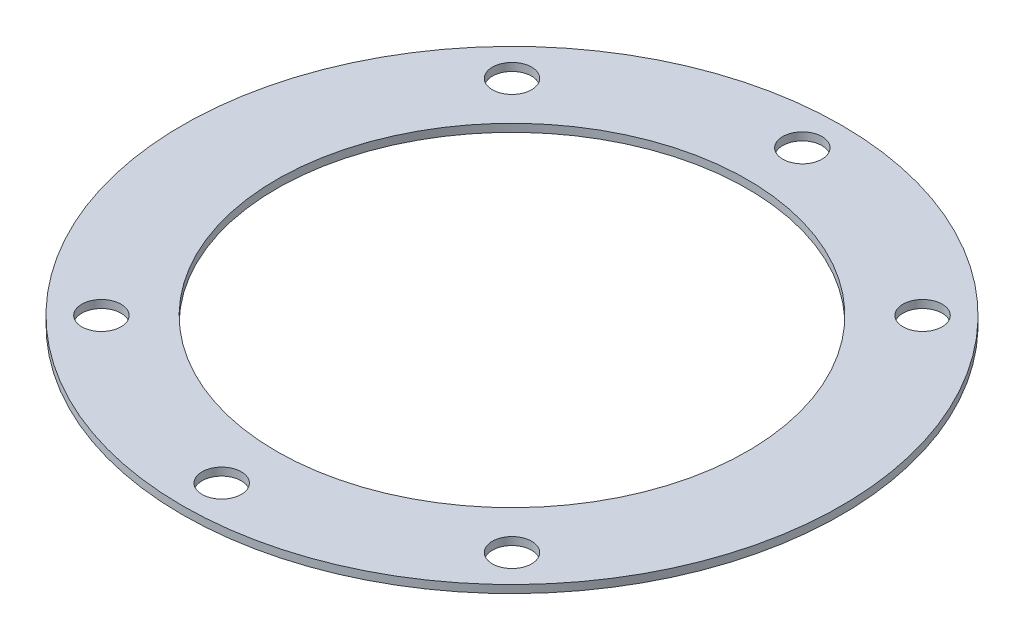
SolidWorks part; units mm, degrees
material "Alliage 1060"
ref_plane "Face" through (0, 0, 0) normal (0, 0, 1) x (1, 0, 0)
ref_plane "Dessus" through (0, 0, 0) normal (0, 1, 0) x (1, 0, 0)
ref_plane "Droite" through (0, 0, 0) normal (1, 0, 0) x (0, 0, -1)
sketch "Esquisse1" plane through (0, 0, 0) normal (1, 0, 0) x (0, 0, -1)
  line L0 (0, 0) -> (0, -70.5308) construction
  line L1 (-30, 0) -> (-42, 0)
  line L3 (-30, 0) -> (-30, 1)
  line L4 (-30, 1) -> (-42, 1)
  line L5 (-42, 1) -> (-42, 0)
  dimension "D1" = 60
  dimension "D3" = 84
  dimension "D4" = 1
revolve "Révolution1" add sketch "Esquisse1" angle 360 about L0
sketch "Esquisse5" plane through (0, 1, 0) normal (0, 1, 0) x (1, 0, 0)
  line L0 (0, 37) -> (0, -37) construction
  line L1 (-26.163, 26.163) -> (26.163, -26.163) construction
  circle A0 centre (0, 0) radius 37 construction
  dimension "D1" = 74
  dimension "D2" = 45
hole_wizard "Diamètre du perçage Ø5.0 (5)1" positions "Esquisse7" profile "Esquisse6" hole size "Ø5.0" standard "Din" end condition through all
sketch "Esquisse7" plane through (0, 1, 0) normal (0, 1, 0) x (1, 0, 0)
  point P0 (0, 37)
  point P3 (0, -37)
sketch "Esquisse6" plane through (0, 1, -37) normal (1, 0, 0) x (0, 0, 1)
  line L0 (0, 0) -> (0, 1)
  line L1 (0, 1) -> (2.5, 1)
  line L2 (2.5, 1) -> (2.5, 0)
  line L5 (2.5, 0) -> (0, 0)
  line L11 (0, -6.35) -> (0, 107.95) construction
  dimension "Diamètre du perçage jusqu'au prochain" = 5
  dimension "Profondeur du perçage jusqu'au prochain" = 1
hole_wizard "Diamètre du perçage Ø5.0 (5)2" positions "Esquisse9" profile "Esquisse8" hole size "Ø5.0" standard "Din" end condition through all
sketch "Esquisse9" plane through (0, 1, 0) normal (0, 1, 0) x (1, 0, 0)
  point P0 (-26.163, 26.163)
sketch "Esquisse8" plane through (-26.163, 1, -26.163) normal (1, 0, 0) x (0, 0, 1)
  line L0 (0, 0) -> (0, 1)
  line L1 (0, 1) -> (2.5, 1)
  line L2 (2.5, 1) -> (2.5, 0)
  line L5 (2.5, 0) -> (0, 0)
  line L11 (0, -6.35) -> (0, 107.95) construction
  dimension "Diamètre du perçage jusqu'au prochain" = 5
  dimension "Profondeur du perçage jusqu'au prochain" = 1
pattern_circular "Répétition circulaire1" count 4 every 90 about axis through (0, 0, 0) along (0, 1, 0) of "Diamètre du perçage Ø5.0 (5)2"
